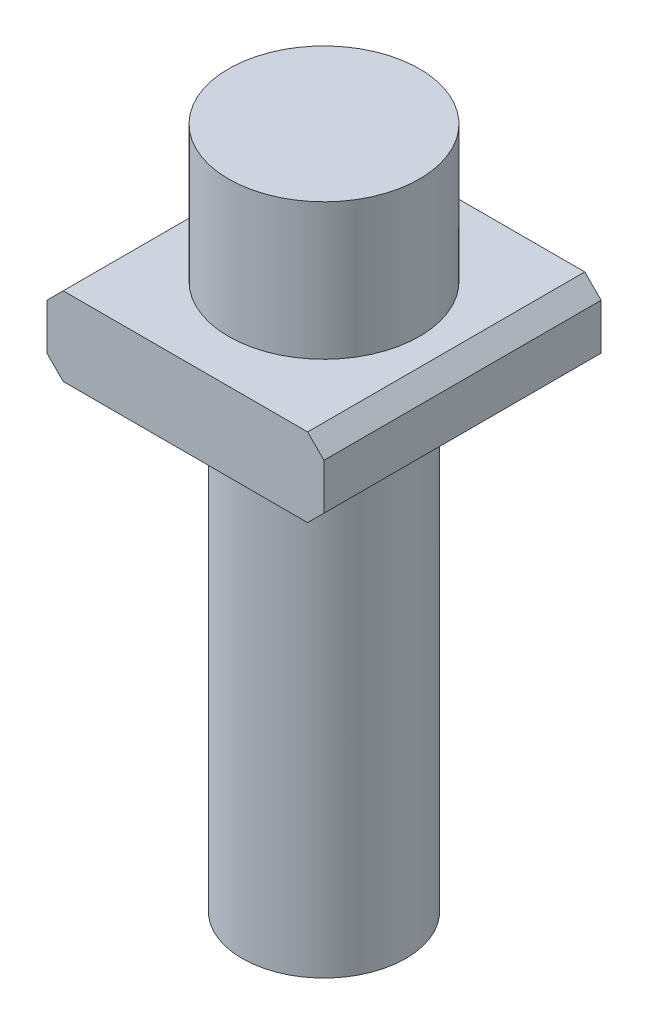
SolidWorks part; units mm, degrees
material "PC High Viscosity"
ref_plane "Front Plane" through (0, 0, 0) normal (0, 0, 1) x (1, 0, 0)
ref_plane "Top Plane" through (0, 0, 0) normal (0, 1, 0) x (1, 0, 0)
ref_plane "Right Plane" through (0, 0, 0) normal (1, 0, 0) x (0, 0, -1)
sketch "Sketch1" plane through (0, 0, 0) normal (0, 1, 0) x (1, 0, 0)
  line L1 (-2.54, 2.54) -> (2.54, 2.54)
  line L2 (-2.54, 2.54) -> (-2.54, -2.54)
  line L3 (-2.54, -2.54) -> (2.54, -2.54)
  line L4 (2.54, 2.54) -> (2.54, -2.54)
  line L5 (-2.54, 2.54) -> (2.54, -2.54) construction
  line L6 (-2.54, -2.54) -> (2.54, 2.54) construction
  point P0 (0, 0)
  dimension "D1" = 5.08
extrude "Boss-Extrude1" add sketch "Sketch1" along normal blind 1.44 contours L3 L4 L1 L2
sketch "Sketch2" plane through (0, 1.44, 0) normal (0, -1, 0) x (1, 0, 0)
  circle A0 centre (0, 0) radius 1.5
  dimension "D1" = 3
extrude "Boss-Extrude2" add sketch "Sketch2" along normal blind 10
sketch "Sketch3" plane through (0, 1.44, 0) normal (0, 1, 0) x (1, 0, 0)
  circle A0 centre (0, 0) radius 1.75
  dimension "D1" = 3.5
extrude "Boss-Extrude3" add sketch "Sketch3" along normal blind 2.5
chamfer "Chamfer1" distance 0.3 angle 45 4 edges at (2.54, 1.44, 0) (2.54, 0, 0) (-2.54, 1.44, 0) (-2.54, 0, 0)
